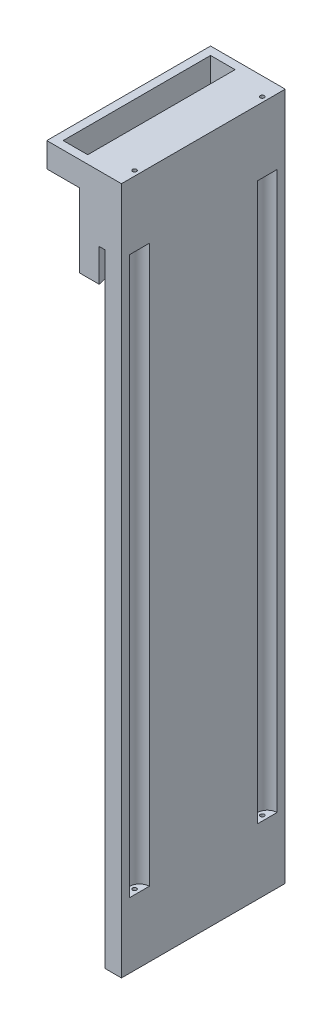
SolidWorks part; units mm, degrees
ref_plane "Front Plane" through (0, 0, 0) normal (0, 0, 1) x (1, 0, 0)
ref_plane "Top Plane" through (0, 0, 0) normal (0, 1, 0) x (1, 0, 0)
ref_plane "Right Plane" through (0, 0, 0) normal (1, 0, 0) x (0, 0, -1)
sketch "Sketch1" plane through (0, 0, 0) normal (0, 0, 1) x (1, 0, 0)
  line L0 (0, 0) -> (0, 30)
  line L1 (0, 30) -> (12.8, 30)
  line L2 (12.8, 30) -> (12.8, 0)
  line L3 (12.8, 0) -> (7.8, 0)
  line L4 (7.8, 0) -> (7.8, 10)
  line L5 (7.8, 10) -> (6, 10)
  line L6 (6, 10) -> (6, 0)
  line L7 (6, 0) -> (0, 0)
  dimension "D1" = 1.8
  dimension "D2" = 6
  dimension "D3" = 5
  dimension "D4" = 30
  dimension "D5" = 10
extrude "Boss-Extrude1" add sketch "Sketch1" along normal blind 50
sketch "Sketch3" plane through (0, 0, 0) normal (0, -1, 0) x (1, 0, 0)
  line L0 (7.8, 50) -> (12.8, 50)
  line L1 (12.8, 50) -> (12.8, 0)
  line L2 (12.8, 0) -> (7.8, 0)
  line L3 (7.8, 0) -> (7.8, 50)
extrude "Boss-Extrude3" add sketch "Sketch3" along normal blind 180
sketch "Esboço2" plane through (0, 0, 0) normal (0, -1, 0) x (1, 0, 0)
  line L0 (6, 50) -> (6, 0)
  arc A0 (6, 50) -> (6, 0) centre (99.3089, 25) ccw
  dimension "D1" = 96.6
extrude "Corte-extrusão1" cut sketch "Esboço2" against normal blind 10
sketch "Esboço3" plane through (0, 0, 0) normal (-1, 0, 0) x (0, 0, 1)
  line L0 (50, 30) -> (50, 0) construction
  line L1 (0, 30) -> (50, 30)
  line L2 (0, 30) -> (0, 22.5)
  line L3 (0, 22.5) -> (50, 22.5)
  line L4 (50, 30) -> (50, 22.5)
  dimension "D1" = 7.5
extrude "Ressalto-extrusão2" add sketch "Esboço3" along normal blind 10
sketch "Esboço4" plane through (0, 22.5, 0) normal (0, -1, 0) x (1, 0, 0)
  line L0 (0, 0) -> (0, 50) construction
  line L1 (0, 47.5) -> (-7.5, 47.5)
  line L2 (0, 47.5) -> (0, 2.5)
  line L3 (0, 2.5) -> (-7.5, 2.5)
  line L4 (-7.5, 47.5) -> (-7.5, 2.5)
  line L5 (-10, 50) -> (0, 50) construction
  line L6 (-10, 0) -> (0, 0) construction
  dimension "D1" = 7.5
  dimension "D2" = 2.5
  dimension "D3" = 2.5
extrude "Corte-extrusão2" cut sketch "Esboço4" against normal blind 10
sketch "Esboço5" plane through (0, 30, 0) normal (0, 1, 0) x (1, 0, 0)
  line L0 (12.8, -50) -> (12.8, 0) construction
  line L1 (12.8, -41.5001) -> (12.8, -47.5)
  arc A0 (12.8, -47.5) -> (12.8, -41.5001) centre (12.8168, -44.5) cw
  dimension "D2" = 3
  dimension "D1" = 2.5
extrude "Corte-extrusão3" cut sketch "Esboço5" against normal blind 170 from offset 20 offset against normal yes
sketch "Esboço6" plane through (0, 30, 0) normal (0, 1, 0) x (1, 0, 0)
  line L0 (12.8, -50) -> (-10, -50) construction
  line L1 (12.8, -50) -> (12.8, 0) construction
  circle A0 centre (11.3, -44.5) radius 0.6
  dimension "D1" = 1.2
  dimension "D2" = 5.5
  dimension "D3" = 1.5
extrude "Corte-extrusão4" cut sketch "Esboço6" against normal blind 195
pattern_linear "Padrão linear1" count 2 spacing 39 along (0, 0, -1) of "Corte-extrusão3", "Corte-extrusão4"
